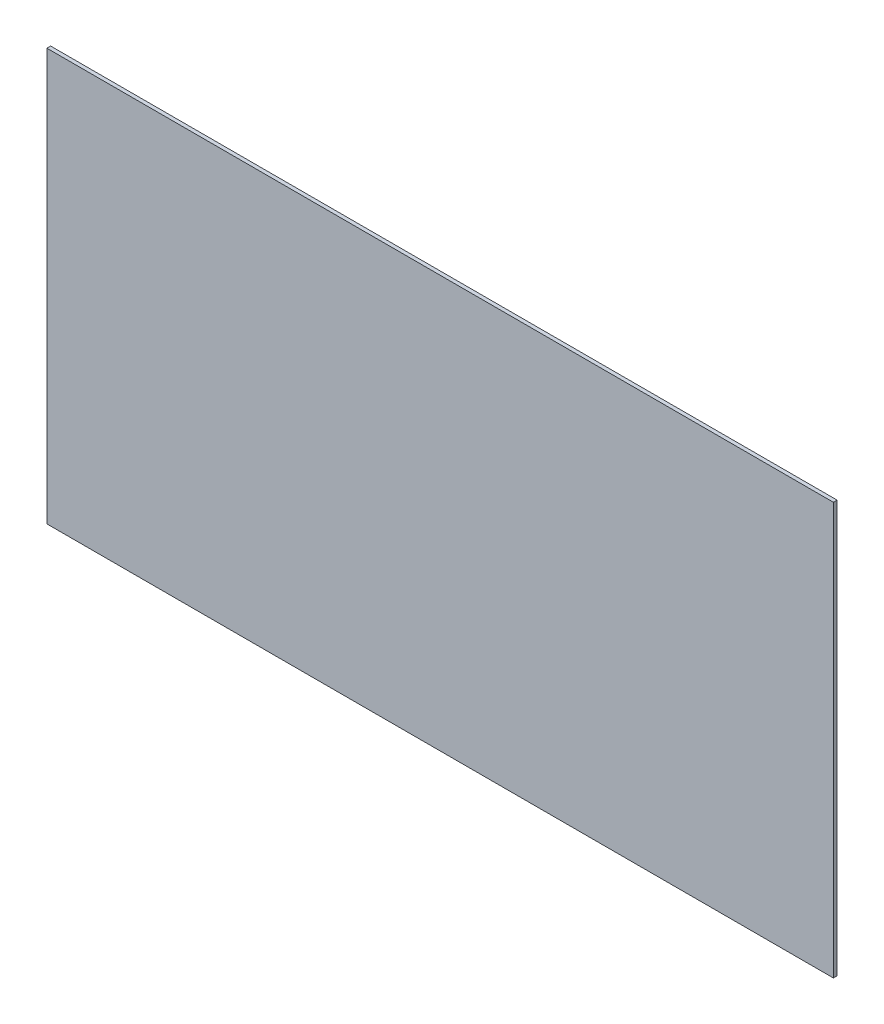
SolidWorks part; units mm, degrees
ref_plane "Plan de face" through (0, 0, 0) normal (0, 0, 1) x (1, 0, 0)
ref_plane "Plan de dessus" through (0, 0, 0) normal (0, 1, 0) x (1, 0, 0)
ref_plane "Plan de droite" through (0, 0, 0) normal (1, 0, 0) x (0, 0, -1)
sketch "Esquisse1" plane through (0, 0, 0) normal (0, 0, 1) x (1, 0, 0)
  line L1 (0, 0) -> (630, 0)
  line L2 (0, 0) -> (0, 330)
  line L3 (0, 330) -> (630, 330)
  line L4 (630, 0) -> (630, 330)
  dimension "D1" = 330
  dimension "D2" = 630
extrude "Boss.-Extru.1" add sketch "Esquisse1" along normal blind 3
